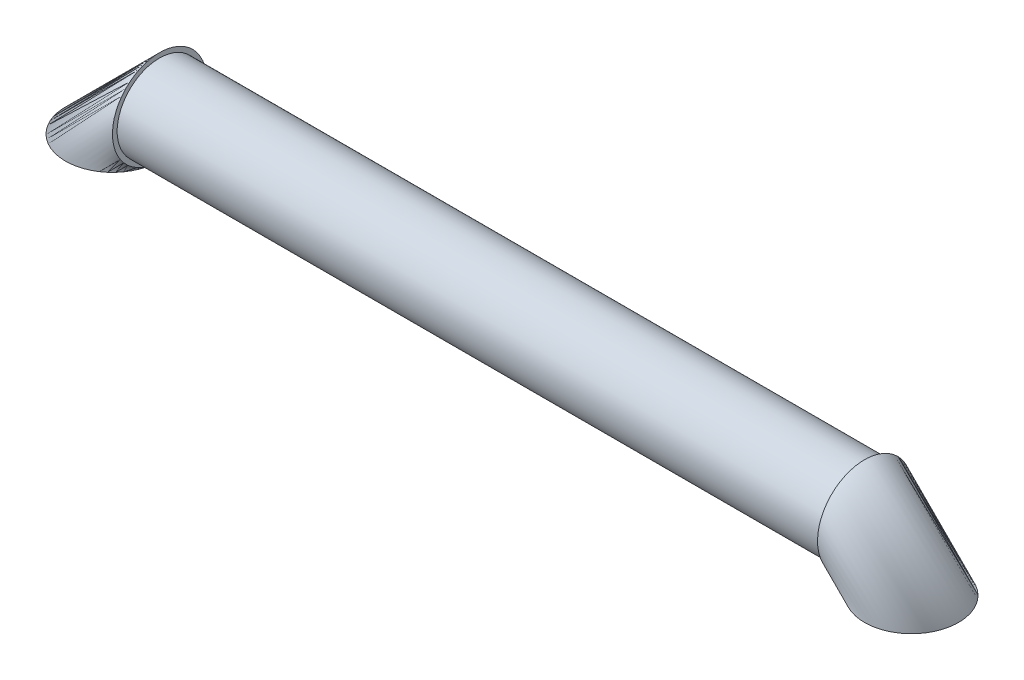
SolidWorks part; units mm, degrees
material "1060 Alloy"
ref_plane "Front Plane" through (0, 0, 0) normal (0, 0, 1) x (1, 0, 0)
ref_plane "Top Plane" through (0, 0, 0) normal (0, 1, 0) x (1, 0, 0)
ref_plane "Right Plane" through (0, 0, 0) normal (1, 0, 0) x (0, 0, -1)
sketch "Sketch2" plane through (0, 0, 0) normal (0, 1, 0) x (1, 0, 0)
  circle A0 centre (0, 0) radius 50
  dimension "D1" = 100
sketch "Sketch4" plane through (0, 0, 0) normal (0, 0, 1) x (1, 0, 0)
  line L0 (50, 0) -> (-50, 0) construction
  line L1 (50, 0) -> (-50, 0) construction
  line L2 (50, 50) -> (50, 0) construction
  arc A0 (0, 0) -> (50, 50) centre (50, 0) cw
sweep "Sweep1" add profiles "Sketch2" path "Sketch4"
sketch "Sketch5" plane through (50, 0, 0) normal (1, 0, 0) x (0, 0, -1)
  circle A1 centre (0, 50) radius 50
  circle A2 centre (0, 50) radius 50
  dimension "D1" = 0
extrude "Boss-Extrude1" add sketch "Sketch5" along normal blind 750
ref_plane "Plane1" through (50, 0, 0) normal (1, 0, 0) x (0, 0, -1)
ref_plane "Plane2" through (425, 0, 0) normal (1, 0, 0) x (0, 0, -1)
mirror "Mirror1" about plane through (425, 0, 0) normal (1, 0, 0) of "Sweep1"
sketch "Sketch6" plane through (50, 0, 0) normal (1, 0, 0) x (0, 0, -1)
  circle A0 centre (0, 50) radius 50 construction
  circle A1 centre (0, 50) radius 50
  circle A2 centre (0, 50) radius 45
  dimension "D1" = 90
ref_plane "Plane3" through (800, 0, 0) normal (1, 0, 0) x (0, 0, -1)
extrude "Cut-Extrude1" cut sketch "Sketch6" along normal up to surface (750 mm away)
